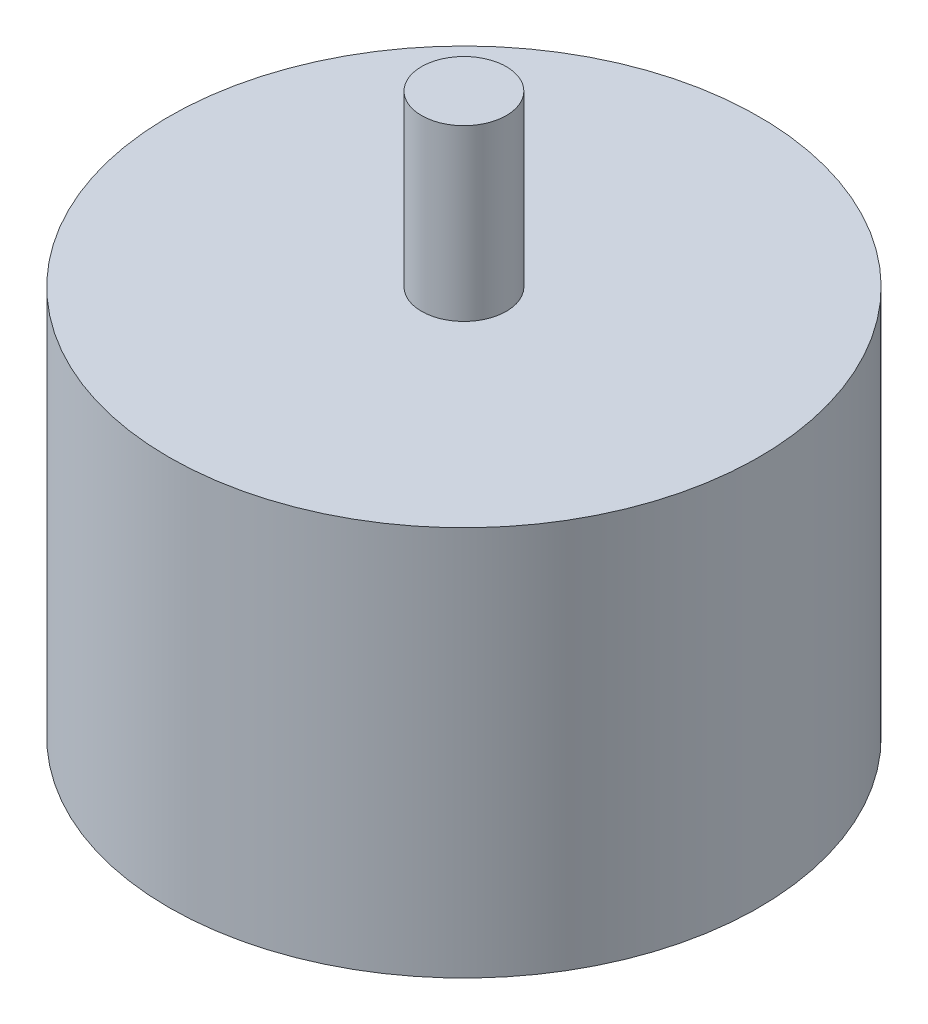
SolidWorks part; units mm, degrees
ref_plane "Front Plane" through (0, 0, 0) normal (0, 0, 1) x (1, 0, 0)
ref_plane "Top Plane" through (0, 0, 0) normal (0, 1, 0) x (1, 0, 0)
ref_plane "Right Plane" through (0, 0, 0) normal (1, 0, 0) x (0, 0, -1)
sketch "Sketch1" plane through (0, 0, 0) normal (0, 1, 0) x (1, 0, 0)
  circle A0 centre (0, 0) radius 17.399
  dimension "D1" = 34.798
extrude "Boss-Extrude1" add sketch "Sketch1" along normal blind 23
sketch "Sketch2" plane through (0, 23, 0) normal (0, 1, 0) x (1, 0, 0)
  circle A0 centre (0, 0) radius 2.5
  dimension "D1" = 5
extrude "Boss-Extrude2" add sketch "Sketch2" along normal blind 10
sketch "Sketch3" plane through (0, 0, 0) normal (0, -1, 0) x (1, 0, 0)
  circle A0 centre (0, 0) radius 1.5
  dimension "D1" = 3
extrude "Boss-Extrude3" add sketch "Sketch3" along normal blind 2
sketch "Sketch4" plane through (0, 0, 0) normal (0, -1, 0) x (1, 0, 0)
  line L0 (0, 0) -> (0, 8.6454) construction
  line L1 (0, 0) -> (7.4808, 0) construction
  circle A0 centre (0, 12.5) radius 1.524
  circle A1 centre (9.5, 0) radius 1.5
  circle A2 centre (-9.5, 0) radius 1.5
  circle A3 centre (0, -12.5) radius 1.524
  dimension "D1" = 3.048
  dimension "D2" = 3
  dimension "D3" = 9.5
  dimension "D4" = 12.5
extrude "Cut-Extrude1" cut sketch "Sketch4" against normal blind 2
equation "\"Motor Y\"= \"Motor Screw Y@Quad Assemb.sldasm\""
equation "\"D4@Sketch4\"=\"Motor Y\"/2"
equation "\"Motor X\"= \"Motor Screw X@Quad Assemb.sldasm\""
equation "\"D3@Sketch4\"=\"Motor X\"/2"
equation "\"Motor Diam\"= \"Motor Diam@Quad Assemb.sldasm\""
equation "\"D1@Sketch1\"=\"Motor Diam\""
equation "\"D1@Boss-Extrude1\"=\"Motor Length@Quad Assemb.sldasm\""
equation "\"D1@Sketch3\"=\"motor shaft diam@quad assemb.sldasm\""
